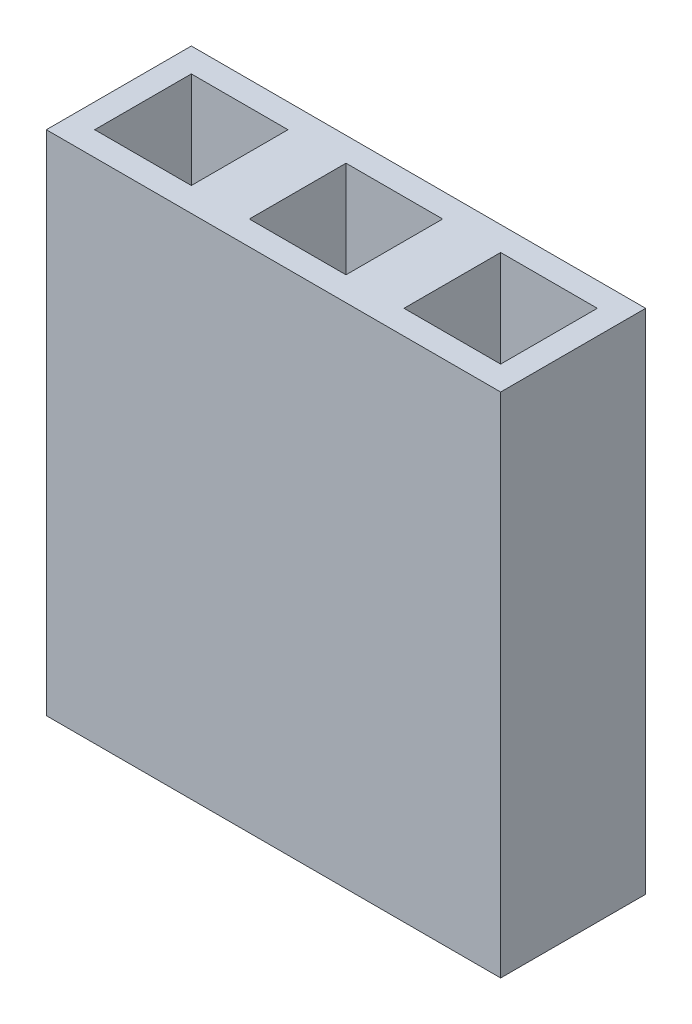
SolidWorks part; units mm, degrees
ref_plane "Plano frontal" through (0, 0, 0) normal (0, 0, 1) x (1, 0, 0)
ref_plane "Plano superior" through (0, 0, 0) normal (0, 1, 0) x (1, 0, 0)
ref_plane "Plano direito" through (0, 0, 0) normal (1, 0, 0) x (0, 0, -1)
sketch "Esboço1" plane through (0, 0, 0) normal (0, 0, 1) x (1, 0, 0)
  line L1 (-19.2, 4.2) -> (19.2, 4.2)
  line L2 (-19.2, 4.2) -> (-19.2, -4.2)
  line L3 (-19.2, -4.2) -> (19.2, -4.2)
  line L4 (19.2, 4.2) -> (19.2, -4.2)
  line L5 (-19.2, 4.2) -> (19.2, -4.2) construction
  line L6 (-19.2, -4.2) -> (19.2, 4.2) construction
  point P0 (0, 0)
  dimension "D1" = 38.4
  dimension "D2" = 8.4
extrude "Ressalto-extrusão1" add sketch "Esboço1" along normal blind 2.4
sketch "Esboço2" plane through (0, 4.2, 0) normal (0, 1, 0) x (1, 0, 0)
  line L0 (19.2, 0) -> (-19.2, 0) construction
  line L1 (-18.8, -0.4) -> (-17.2, -0.4)
  line L2 (-18.8, -0.4) -> (-18.8, -2)
  line L3 (-18.8, -2) -> (-17.2, -2)
  line L4 (-17.2, -0.4) -> (-17.2, -2)
  line L5 (-19.2, -2.4) -> (-19.2, 0) construction
  dimension "D1" = 1.6
  dimension "D2" = 1.6
  dimension "D3" = 0.4
  dimension "D4" = 0.4
extrude "Corte-extrusão1" cut sketch "Esboço2" against normal blind 2.5
pattern_linear "Padrão linear1" count 16 spacing 2.56 along (1, 0, 0) of "Corte-extrusão1"
sketch "Esboço3" plane through (0, 1.7, 0) normal (0, 1, 0) x (1, 0, 0)
  line L0 (-18.8, -0.4) -> (-17.2, -2) construction
  line L1 (-17.2, -0.4) -> (-18.8, -2) construction
  line L4 (-18.8, -0.4) -> (-18.8, -2)
  line L5 (-18.8, -2) -> (-17.2, -2)
  line L6 (-17.2, -2) -> (-17.2, -0.4)
  line L7 (-17.2, -0.4) -> (-18.8, -0.4)
  line L8 (-18.8, -0.4) -> (-18.8, -2)
  line L9 (-18.8, -2) -> (-17.2, -2)
  line L10 (-17.2, -2) -> (-17.2, -0.4)
  line L11 (-17.2, -0.4) -> (-18.8, -0.4)
  circle A0 centre (-18, -1.2) radius 0.51
  dimension "D2" = 1.02
  dimension "D1" = 0
extrude "Corte-extrusão2" cut sketch "Esboço3" against normal through all contours A0
pattern_linear "Padrão linear2" count 15 spacing 2.543 along (1, 0, 0) of "Corte-extrusão2"
sketch "Esboço6" plane through (0, 0, 2.4) normal (0, 0, 1) x (1, 0, 0)
  line L0 (1.1198, 4.2) -> (1.1198, -4.2)
  line L1 (19.2, 4.2) -> (-19.2, 4.2) construction
  line L2 (-19.2, -4.2) -> (19.2, -4.2) construction
  line L3 (1.1198, -4.2) -> (19.2, -4.2)
  line L4 (19.2, -4.2) -> (19.2, 4.2)
  line L5 (19.2, 4.2) -> (1.1198, 4.2)
extrude "Corte-extrusão3" cut sketch "Esboço6" against normal blind 10
sketch "Esboço8" plane through (0, 0, 2.4) normal (0, 0, 1) x (1, 0, 0)
  line L0 (-11.68, 4.2) -> (-11.68, -4.2)
  line L1 (-11.68, 4.2) -> (1.1198, 4.2) construction
  line L2 (-19.2, -4.2) -> (1.1198, -4.2) construction
  line L3 (-11.68, -4.2) -> (1.1198, -4.2)
  line L4 (1.1198, -4.2) -> (1.1198, 4.2)
  line L5 (1.1198, 4.2) -> (-11.68, 4.2)
extrude "Corte-extrusão4" cut sketch "Esboço8" against normal blind 10
